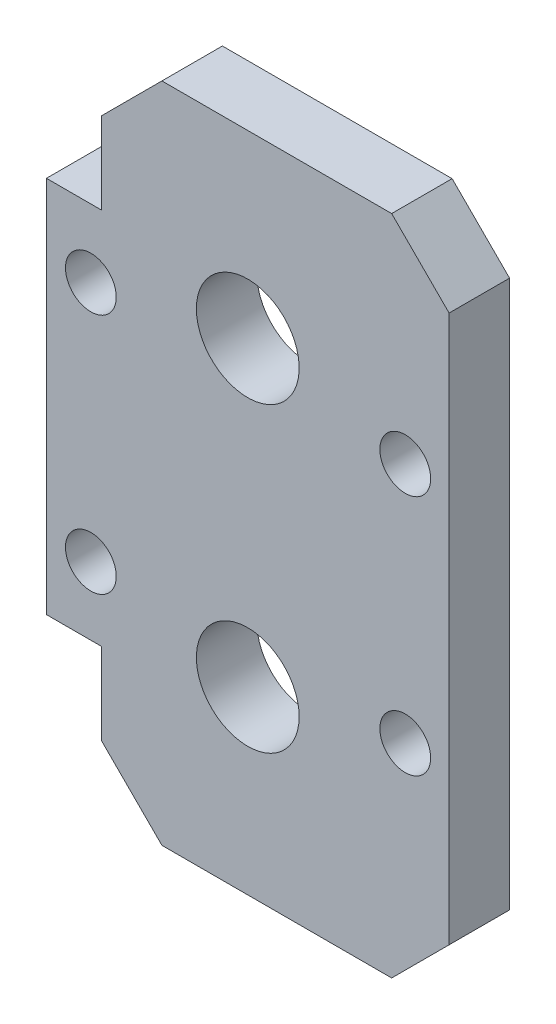
SolidWorks part; units mm, degrees
ref_plane "Front Plane" through (0, 0, 0) normal (0, 0, 1) x (1, 0, 0)
ref_plane "Top Plane" through (0, 0, 0) normal (0, 1, 0) x (1, 0, 0)
ref_plane "Right Plane" through (0, 0, 0) normal (1, 0, 0) x (0, 0, -1)
sketch "Sketch1" plane through (0, 0, 0) normal (0, 0, 1) x (1, 0, 0)
  line L0 (11.9001, -27.375) -> (16.6501, -22.625)
  line L1 (16.6501, -22.625) -> (16.6501, 22.625)
  line L12 (-12.0999, -15.625) -> (-12.0999, -22.375)
  line L13 (-12.0999, -22.375) -> (-7.0999, -27.375)
  line L14 (-7.0999, -27.375) -> (11.9001, -27.375)
  line L16 (0, 0) -> (38.6, 0) construction
  line L17 (0, -8.3776) -> (0, 8.3776) construction
  line L18 (-16.65, -15.625) -> (-12.0999, -15.625)
  line L19 (-16.65, -15.625) -> (-16.65, 15.625)
  line L20 (-16.65, 15.625) -> (-12.0999, 15.625)
  line L21 (-7.0999, 27.375) -> (11.9001, 27.375)
  line L22 (-12.0999, 22.375) -> (-7.0999, 27.375)
  line L23 (-12.0999, 15.625) -> (-12.0999, 22.375)
  line L24 (11.9001, 27.375) -> (16.6501, 22.625)
  circle A8 centre (0, -12.485) radius 4.25
  circle A12 centre (0, 12.485) radius 4.25
  point P5 (0, 0)
  point P20 (-16.65, 0)
  point P26 (16.6501, 0)
  dimension "D4" = 27.375
  dimension "D5" = 12.485
  dimension "D6" = 16.6501
  dimension "D7" = 8.5
  dimension "D8" = 33.3001
  dimension "D3" = 22.625
  dimension "D18" = 6.7175
  dimension "D19" = 19
  dimension "D20" = 7.0711
  dimension "D21" = 6.75
  dimension "D22" = 4.5501
extrude "Boss-Extrude1" add sketch "Sketch1" along normal blind 5
sketch "Sketch2" plane through (0, 0, 0) normal (0, 0, -1) x (-1, 0, 0)
  line L0 (0, 0) -> (-10.6752, 0) construction
  line L1 (0, 0) -> (0, -20.8467) construction
  circle A1 centre (-13.0237, -10.0013) radius 2.1
  circle A3 centre (-13.0237, 9.9987) radius 2.1
  circle A5 centre (12.9763, -10.0013) radius 2.1
  circle A7 centre (12.9763, 9.9987) radius 2.1
  point P7 (0, 0)
  point P13 (0, 0)
  point P14 (0, 0)
  point P15 (0, 0)
  point P16 (0, 0)
  dimension "D3" = 4.2
  dimension "D4" = 4.2
  dimension "D5" = 4.2
  dimension "D6" = 4.2
  dimension "D1" = 13.0237
  dimension "D2" = 10.0013
  dimension "D7" = 20
  dimension "D8" = 26
extrude "Cut-Extrude1" cut sketch "Sketch2" against normal blind 10
